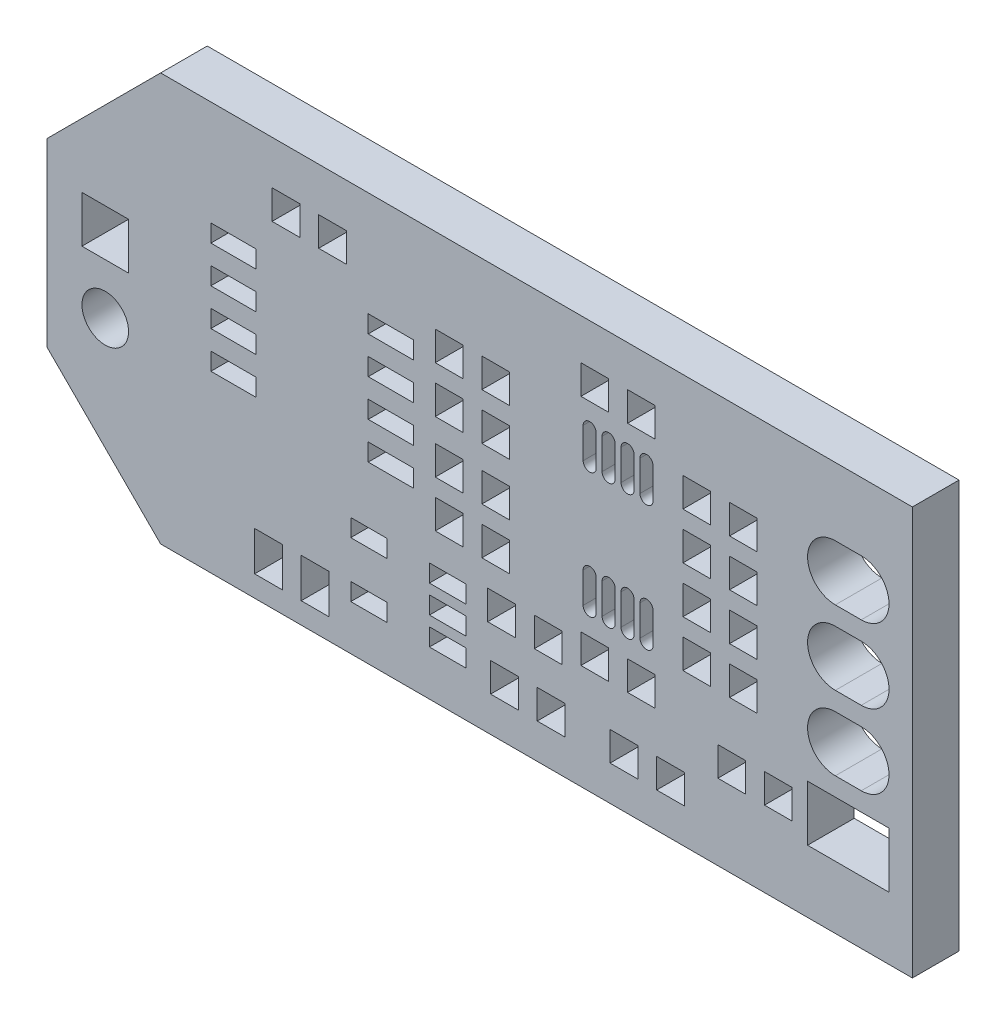
SolidWorks part; units mm, degrees
ref_plane "Front Plane" through (0, 0, 0) normal (0, 0, 1) x (1, 0, 0)
ref_plane "Top Plane" through (0, 0, 0) normal (0, 1, 0) x (1, 0, 0)
ref_plane "Right Plane" through (0, 0, 0) normal (1, 0, 0) x (0, 0, -1)
sketch "Model" plane through (0, 0, 0) normal (0, 0, 1) x (1, 0, 0)
  line L0 (-135.5251, 26.45) -> (-135.5251, 25.85)
  line L1 (-135.5251, 25.85) -> (-136.775, 25.85)
  line L2 (-136.775, 25.85) -> (-136.775, 26.45)
  line L3 (-136.775, 26.45) -> (-135.5251, 26.45)
  line L4 (-135.5251, 27.4) -> (-135.5251, 26.8)
  line L5 (-135.5251, 26.8) -> (-136.775, 26.8)
  line L6 (-136.775, 26.8) -> (-136.775, 27.4)
  line L7 (-136.775, 27.4) -> (-135.5251, 27.4)
  line L8 (-135.5251, 28.3499) -> (-135.5251, 27.7501)
  line L9 (-135.5251, 27.7501) -> (-136.775, 27.7501)
  line L10 (-136.775, 27.7501) -> (-136.775, 28.3499)
  line L11 (-136.775, 28.3499) -> (-135.5251, 28.3499)
  line L12 (-138.2251, 28.3499) -> (-138.2251, 27.7501)
  line L13 (-138.2251, 27.7501) -> (-139.475, 27.7501)
  line L14 (-139.475, 27.7501) -> (-139.475, 28.3499)
  line L15 (-139.475, 28.3499) -> (-138.2251, 28.3499)
  line L16 (-138.2251, 26.45) -> (-138.2251, 25.85)
  line L17 (-138.2251, 25.85) -> (-139.475, 25.85)
  line L18 (-139.475, 25.85) -> (-139.475, 26.45)
  line L19 (-139.475, 26.45) -> (-138.2251, 26.45)
  line L22 (-135.25, 28.9) -> (-135.25, 25.3)
  line L23 (-135.25, 25.3) -> (-139.75, 25.3)
  line L24 (-139.75, 25.3) -> (-139.75, 28.9)
  line L25 (-139.75, 28.9) -> (-135.25, 28.9)
  line L26 (-121.003, 26.4475) -> (-123.797, 26.4475)
  line L27 (-123.797, 26.4475) -> (-123.797, 28.3525)
  line L28 (-123.797, 28.3525) -> (-121.003, 28.3525)
  line L29 (-121.003, 28.3525) -> (-121.003, 26.4475)
  line L30 (-122.8445, 30.8925) -> (-121.9555, 30.8925)
  line L31 (-121.9555, 28.9875) -> (-122.8445, 28.9875)
  line L32 (-122.8445, 33.4325) -> (-121.9555, 33.4325)
  line L33 (-121.9555, 31.5275) -> (-122.8445, 31.5275)
  line L34 (-122.8445, 35.9725) -> (-121.9555, 35.9725)
  line L35 (-121.9555, 34.0675) -> (-122.8445, 34.0675)
  line L38 (-148.7, 33.4) -> (-147.1, 33.4)
  line L39 (-147.1, 33.4) -> (-147.1, 31.8)
  line L40 (-147.1, 31.8) -> (-148.7, 31.8)
  line L41 (-148.7, 31.8) -> (-148.7, 33.4)
  line L44 (-149.295, 33.995) -> (-146.505, 33.995)
  line L45 (-146.505, 33.995) -> (-146.505, 28.665)
  line L46 (-146.505, 28.665) -> (-149.295, 28.665)
  line L47 (-149.295, 28.665) -> (-149.295, 33.995)
  line L48 (-141.825, 25.025) -> (-142.775, 25.025)
  line L49 (-142.775, 25.025) -> (-142.775, 26.375)
  line L50 (-142.775, 26.375) -> (-141.825, 26.375)
  line L51 (-141.825, 26.375) -> (-141.825, 25.025)
  line L52 (-140.225, 25.025) -> (-141.175, 25.025)
  line L53 (-141.175, 25.025) -> (-141.175, 26.375)
  line L54 (-141.175, 26.375) -> (-140.225, 26.375)
  line L55 (-140.225, 26.375) -> (-140.225, 25.025)
  line L58 (-142.9, 24.85) -> (-142.9, 26.55)
  line L59 (-142.9, 26.55) -> (-140.1, 26.55)
  line L60 (-140.1, 26.55) -> (-140.1, 24.85)
  line L61 (-140.1, 24.85) -> (-142.9, 24.85)
  line L62 (-131.05, 30.775) -> (-131.05, 29.725)
  line L63 (-131.5, 29.725) -> (-131.5, 30.775)
  line L64 (-130.4, 30.775) -> (-130.4, 29.725)
  line L65 (-130.85, 29.725) -> (-130.85, 30.775)
  line L66 (-129.75, 30.775) -> (-129.75, 29.725)
  line L67 (-130.2, 29.725) -> (-130.2, 30.775)
  line L68 (-129.1, 30.775) -> (-129.1, 29.725)
  line L69 (-129.55, 29.725) -> (-129.55, 30.775)
  line L70 (-129.1, 35.075) -> (-129.1, 34.025)
  line L71 (-129.55, 34.025) -> (-129.55, 35.075)
  line L72 (-129.75, 35.075) -> (-129.75, 34.025)
  line L73 (-130.2, 34.025) -> (-130.2, 35.075)
  line L74 (-130.4, 35.075) -> (-130.4, 34.025)
  line L75 (-130.85, 34.025) -> (-130.85, 35.075)
  line L76 (-131.05, 35.075) -> (-131.05, 34.025)
  line L77 (-131.5, 34.025) -> (-131.5, 35.075)
  line L80 (-128.5, 29.25) -> (-132.1, 29.25)
  line L81 (-132.1, 29.25) -> (-132.1, 35.55)
  line L82 (-132.1, 35.55) -> (-128.5, 35.55)
  line L83 (-128.5, 35.55) -> (-128.5, 29.25)
  line L84 (-125.925, 26.9) -> (-126.875, 26.9)
  line L85 (-126.875, 26.9) -> (-126.875, 27.9)
  line L86 (-126.875, 27.9) -> (-125.925, 27.9)
  line L87 (-125.925, 27.9) -> (-125.925, 26.9)
  line L88 (-124.325, 26.9) -> (-125.275, 26.9)
  line L89 (-125.275, 26.9) -> (-125.275, 27.9)
  line L90 (-125.275, 27.9) -> (-124.325, 27.9)
  line L91 (-124.325, 27.9) -> (-124.325, 26.9)
  line L94 (-127.15, 26.65) -> (-127.15, 28.15)
  line L95 (-127.15, 28.15) -> (-124.05, 28.15)
  line L96 (-124.05, 28.15) -> (-124.05, 26.65)
  line L97 (-124.05, 26.65) -> (-127.15, 26.65)
  line L98 (-133.725, 25.5) -> (-134.675, 25.5)
  line L99 (-134.675, 25.5) -> (-134.675, 26.5)
  line L100 (-134.675, 26.5) -> (-133.725, 26.5)
  line L101 (-133.725, 26.5) -> (-133.725, 25.5)
  line L102 (-132.125, 25.5) -> (-133.075, 25.5)
  line L103 (-133.075, 25.5) -> (-133.075, 26.5)
  line L104 (-133.075, 26.5) -> (-132.125, 26.5)
  line L105 (-132.125, 26.5) -> (-132.125, 25.5)
  line L108 (-134.95, 25.25) -> (-134.95, 26.75)
  line L109 (-134.95, 26.75) -> (-131.85, 26.75)
  line L110 (-131.85, 26.75) -> (-131.85, 25.25)
  line L111 (-131.85, 25.25) -> (-134.95, 25.25)
  line L112 (-133.825, 27.6) -> (-134.775, 27.6)
  line L113 (-134.775, 27.6) -> (-134.775, 28.6)
  line L114 (-134.775, 28.6) -> (-133.825, 28.6)
  line L115 (-133.825, 28.6) -> (-133.825, 27.6)
  line L116 (-132.225, 27.6) -> (-133.175, 27.6)
  line L117 (-133.175, 27.6) -> (-133.175, 28.6)
  line L118 (-133.175, 28.6) -> (-132.225, 28.6)
  line L119 (-132.225, 28.6) -> (-132.225, 27.6)
  line L122 (-135.05, 27.35) -> (-135.05, 28.85)
  line L123 (-135.05, 28.85) -> (-131.95, 28.85)
  line L124 (-131.95, 28.85) -> (-131.95, 27.35)
  line L125 (-131.95, 27.35) -> (-135.05, 27.35)
  line L126 (-128.975, 26.5) -> (-128.025, 26.5)
  line L127 (-128.025, 26.5) -> (-128.025, 25.5)
  line L128 (-128.025, 25.5) -> (-128.975, 25.5)
  line L129 (-128.975, 25.5) -> (-128.975, 26.5)
  line L130 (-130.575, 26.5) -> (-129.625, 26.5)
  line L131 (-129.625, 26.5) -> (-129.625, 25.5)
  line L132 (-129.625, 25.5) -> (-130.575, 25.5)
  line L133 (-130.575, 25.5) -> (-130.575, 26.5)
  line L136 (-127.75, 26.75) -> (-127.75, 25.25)
  line L137 (-127.75, 25.25) -> (-130.85, 25.25)
  line L138 (-130.85, 25.25) -> (-130.85, 26.75)
  line L139 (-130.85, 26.75) -> (-127.75, 26.75)
  line L140 (-127.125, 29.5) -> (-128.075, 29.5)
  line L141 (-128.075, 29.5) -> (-128.075, 30.5)
  line L142 (-128.075, 30.5) -> (-127.125, 30.5)
  line L143 (-127.125, 30.5) -> (-127.125, 29.5)
  line L144 (-125.525, 29.5) -> (-126.475, 29.5)
  line L145 (-126.475, 29.5) -> (-126.475, 30.5)
  line L146 (-126.475, 30.5) -> (-125.525, 30.5)
  line L147 (-125.525, 30.5) -> (-125.525, 29.5)
  line L150 (-128.35, 29.25) -> (-128.35, 30.75)
  line L151 (-128.35, 30.75) -> (-125.25, 30.75)
  line L152 (-125.25, 30.75) -> (-125.25, 29.25)
  line L153 (-125.25, 29.25) -> (-128.35, 29.25)
  line L154 (-127.125, 34.3) -> (-128.075, 34.3)
  line L155 (-128.075, 34.3) -> (-128.075, 35.3)
  line L156 (-128.075, 35.3) -> (-127.125, 35.3)
  line L157 (-127.125, 35.3) -> (-127.125, 34.3)
  line L158 (-125.525, 34.3) -> (-126.475, 34.3)
  line L159 (-126.475, 34.3) -> (-126.475, 35.3)
  line L160 (-126.475, 35.3) -> (-125.525, 35.3)
  line L161 (-125.525, 35.3) -> (-125.525, 34.3)
  line L164 (-128.35, 34.05) -> (-128.35, 35.55)
  line L165 (-128.35, 35.55) -> (-125.25, 35.55)
  line L166 (-125.25, 35.55) -> (-125.25, 34.05)
  line L167 (-125.25, 34.05) -> (-128.35, 34.05)
  line L168 (-127.125, 31.1) -> (-128.075, 31.1)
  line L169 (-128.075, 31.1) -> (-128.075, 32.1)
  line L170 (-128.075, 32.1) -> (-127.125, 32.1)
  line L171 (-127.125, 32.1) -> (-127.125, 31.1)
  line L172 (-125.525, 31.1) -> (-126.475, 31.1)
  line L173 (-126.475, 31.1) -> (-126.475, 32.1)
  line L174 (-126.475, 32.1) -> (-125.525, 32.1)
  line L175 (-125.525, 32.1) -> (-125.525, 31.1)
  line L178 (-128.35, 30.85) -> (-128.35, 32.35)
  line L179 (-128.35, 32.35) -> (-125.25, 32.35)
  line L180 (-125.25, 32.35) -> (-125.25, 30.85)
  line L181 (-125.25, 30.85) -> (-128.35, 30.85)
  line L182 (-127.125, 32.7) -> (-128.075, 32.7)
  line L183 (-128.075, 32.7) -> (-128.075, 33.7)
  line L184 (-128.075, 33.7) -> (-127.125, 33.7)
  line L185 (-127.125, 33.7) -> (-127.125, 32.7)
  line L186 (-125.525, 32.7) -> (-126.475, 32.7)
  line L187 (-126.475, 32.7) -> (-126.475, 33.7)
  line L188 (-126.475, 33.7) -> (-125.525, 33.7)
  line L189 (-125.525, 33.7) -> (-125.525, 32.7)
  line L192 (-128.35, 32.45) -> (-128.35, 33.95)
  line L193 (-128.35, 33.95) -> (-125.25, 33.95)
  line L194 (-125.25, 33.95) -> (-125.25, 32.45)
  line L195 (-125.25, 32.45) -> (-128.35, 32.45)
  line L196 (-135.625, 34.4) -> (-136.575, 34.4)
  line L197 (-136.575, 34.4) -> (-136.575, 35.4)
  line L198 (-136.575, 35.4) -> (-135.625, 35.4)
  line L199 (-135.625, 35.4) -> (-135.625, 34.4)
  line L200 (-134.025, 34.4) -> (-134.975, 34.4)
  line L201 (-134.975, 34.4) -> (-134.975, 35.4)
  line L202 (-134.975, 35.4) -> (-134.025, 35.4)
  line L203 (-134.025, 35.4) -> (-134.025, 34.4)
  line L206 (-136.85, 34.15) -> (-136.85, 35.65)
  line L207 (-136.85, 35.65) -> (-133.75, 35.65)
  line L208 (-133.75, 35.65) -> (-133.75, 34.15)
  line L209 (-133.75, 34.15) -> (-136.85, 34.15)
  line L210 (-135.625, 29.4) -> (-136.575, 29.4)
  line L211 (-136.575, 29.4) -> (-136.575, 30.4)
  line L212 (-136.575, 30.4) -> (-135.625, 30.4)
  line L213 (-135.625, 30.4) -> (-135.625, 29.4)
  line L214 (-134.025, 29.4) -> (-134.975, 29.4)
  line L215 (-134.975, 29.4) -> (-134.975, 30.4)
  line L216 (-134.975, 30.4) -> (-134.025, 30.4)
  line L217 (-134.025, 30.4) -> (-134.025, 29.4)
  line L220 (-136.85, 29.15) -> (-136.85, 30.65)
  line L221 (-136.85, 30.65) -> (-133.75, 30.65)
  line L222 (-133.75, 30.65) -> (-133.75, 29.15)
  line L223 (-133.75, 29.15) -> (-136.85, 29.15)
  line L224 (-130.625, 35.9) -> (-131.575, 35.9)
  line L225 (-131.575, 35.9) -> (-131.575, 36.9)
  line L226 (-131.575, 36.9) -> (-130.625, 36.9)
  line L227 (-130.625, 36.9) -> (-130.625, 35.9)
  line L228 (-129.025, 35.9) -> (-129.975, 35.9)
  line L229 (-129.975, 35.9) -> (-129.975, 36.9)
  line L230 (-129.975, 36.9) -> (-129.025, 36.9)
  line L231 (-129.025, 36.9) -> (-129.025, 35.9)
  line L234 (-131.85, 35.65) -> (-131.85, 37.15)
  line L235 (-131.85, 37.15) -> (-128.75, 37.15)
  line L236 (-128.75, 37.15) -> (-128.75, 35.65)
  line L237 (-128.75, 35.65) -> (-131.85, 35.65)
  line L238 (-130.625, 27.9) -> (-131.575, 27.9)
  line L239 (-131.575, 27.9) -> (-131.575, 28.9)
  line L240 (-131.575, 28.9) -> (-130.625, 28.9)
  line L241 (-130.625, 28.9) -> (-130.625, 27.9)
  line L242 (-129.025, 27.9) -> (-129.975, 27.9)
  line L243 (-129.975, 27.9) -> (-129.975, 28.9)
  line L244 (-129.975, 28.9) -> (-129.025, 28.9)
  line L245 (-129.025, 28.9) -> (-129.025, 27.9)
  line L248 (-131.85, 27.65) -> (-131.85, 29.15)
  line L249 (-131.85, 29.15) -> (-128.75, 29.15)
  line L250 (-128.75, 29.15) -> (-128.75, 27.65)
  line L251 (-128.75, 27.65) -> (-131.85, 27.65)
  line L252 (-134.975, 32) -> (-134.025, 32)
  line L253 (-134.025, 32) -> (-134.025, 31)
  line L254 (-134.025, 31) -> (-134.975, 31)
  line L255 (-134.975, 31) -> (-134.975, 32)
  line L256 (-136.575, 32) -> (-135.625, 32)
  line L257 (-135.625, 32) -> (-135.625, 31)
  line L258 (-135.625, 31) -> (-136.575, 31)
  line L259 (-136.575, 31) -> (-136.575, 32)
  line L262 (-133.75, 32.25) -> (-133.75, 30.75)
  line L263 (-133.75, 30.75) -> (-136.85, 30.75)
  line L264 (-136.85, 30.75) -> (-136.85, 32.25)
  line L265 (-136.85, 32.25) -> (-133.75, 32.25)
  line L266 (-134.975, 33.8) -> (-134.025, 33.8)
  line L267 (-134.025, 33.8) -> (-134.025, 32.8)
  line L268 (-134.025, 32.8) -> (-134.975, 32.8)
  line L269 (-134.975, 32.8) -> (-134.975, 33.8)
  line L270 (-136.575, 33.8) -> (-135.625, 33.8)
  line L271 (-135.625, 33.8) -> (-135.625, 32.8)
  line L272 (-135.625, 32.8) -> (-136.575, 32.8)
  line L273 (-136.575, 32.8) -> (-136.575, 33.8)
  line L276 (-133.75, 34.05) -> (-133.75, 32.55)
  line L277 (-133.75, 32.55) -> (-136.85, 32.55)
  line L278 (-136.85, 32.55) -> (-136.85, 34.05)
  line L279 (-136.85, 34.05) -> (-133.75, 34.05)
  line L280 (-141.225, 35.8) -> (-142.175, 35.8)
  line L281 (-142.175, 35.8) -> (-142.175, 36.8)
  line L282 (-142.175, 36.8) -> (-141.225, 36.8)
  line L283 (-141.225, 36.8) -> (-141.225, 35.8)
  line L284 (-139.625, 35.8) -> (-140.575, 35.8)
  line L285 (-140.575, 35.8) -> (-140.575, 36.8)
  line L286 (-140.575, 36.8) -> (-139.625, 36.8)
  line L287 (-139.625, 36.8) -> (-139.625, 35.8)
  line L290 (-142.45, 35.55) -> (-142.45, 37.05)
  line L291 (-142.45, 37.05) -> (-139.35, 37.05)
  line L292 (-139.35, 37.05) -> (-139.35, 35.55)
  line L293 (-139.35, 35.55) -> (-142.45, 35.55)
  line L294 (-144.275, 34.105) -> (-144.275, 34.705)
  line L295 (-144.275, 34.705) -> (-142.725, 34.705)
  line L296 (-142.725, 34.705) -> (-142.725, 34.105)
  line L297 (-142.725, 34.105) -> (-144.275, 34.105)
  line L298 (-144.275, 32.835) -> (-144.275, 33.435)
  line L299 (-144.275, 33.435) -> (-142.725, 33.435)
  line L300 (-142.725, 33.435) -> (-142.725, 32.835)
  line L301 (-142.725, 32.835) -> (-144.275, 32.835)
  line L302 (-144.275, 31.565) -> (-144.275, 32.165)
  line L303 (-144.275, 32.165) -> (-142.725, 32.165)
  line L304 (-142.725, 32.165) -> (-142.725, 31.565)
  line L305 (-142.725, 31.565) -> (-144.275, 31.565)
  line L306 (-144.275, 30.295) -> (-144.275, 30.895)
  line L307 (-144.275, 30.895) -> (-142.725, 30.895)
  line L308 (-142.725, 30.895) -> (-142.725, 30.295)
  line L309 (-142.725, 30.295) -> (-144.275, 30.295)
  line L310 (-138.875, 30.295) -> (-138.875, 30.895)
  line L311 (-138.875, 30.895) -> (-137.325, 30.895)
  line L312 (-137.325, 30.895) -> (-137.325, 30.295)
  line L313 (-137.325, 30.295) -> (-138.875, 30.295)
  line L314 (-138.875, 31.565) -> (-138.875, 32.165)
  line L315 (-138.875, 32.165) -> (-137.325, 32.165)
  line L316 (-137.325, 32.165) -> (-137.325, 31.565)
  line L317 (-137.325, 31.565) -> (-138.875, 31.565)
  line L318 (-138.875, 32.835) -> (-138.875, 33.435)
  line L319 (-138.875, 33.435) -> (-137.325, 33.435)
  line L320 (-137.325, 33.435) -> (-137.325, 32.835)
  line L321 (-137.325, 32.835) -> (-138.875, 32.835)
  line L322 (-138.875, 34.105) -> (-138.875, 34.705)
  line L323 (-138.875, 34.705) -> (-137.325, 34.705)
  line L324 (-137.325, 34.705) -> (-137.325, 34.105)
  line L325 (-137.325, 34.105) -> (-138.875, 34.105)
  line L328 (-144.55, 29.75) -> (-144.55, 35.25)
  line L329 (-144.55, 35.25) -> (-137.05, 35.25)
  line L330 (-137.05, 35.25) -> (-137.05, 29.75)
  line L331 (-137.05, 29.75) -> (-144.55, 29.75)
  line L332 (-146, 24.3) -> (-120.2, 24.3)
  line L333 (-120.2, 24.3) -> (-120.2, 38.3)
  line L334 (-120.2, 38.3) -> (-146, 38.3)
  line L335 (-146, 38.3) -> (-149.9, 34.4)
  line L336 (-149.9, 34.4) -> (-149.9, 28.2)
  line L337 (-149.9, 28.2) -> (-146, 24.3)
  circle A0 centre (-147.9, 30.06) radius 0.8
  arc A2 (-121.9555, 28.9875) -> (-121.9555, 30.8925) centre (-121.9555, 29.94) ccw
  arc A3 (-122.8445, 30.8925) -> (-122.8445, 28.9875) centre (-122.8445, 29.94) ccw
  arc A4 (-121.9555, 31.5275) -> (-121.9555, 33.4325) centre (-121.9555, 32.48) ccw
  arc A5 (-122.8445, 33.4325) -> (-122.8445, 31.5275) centre (-122.8445, 32.48) ccw
  arc A6 (-121.9555, 34.0675) -> (-121.9555, 35.9725) centre (-121.9555, 35.02) ccw
  arc A7 (-122.8445, 35.9725) -> (-122.8445, 34.0675) centre (-122.8445, 35.02) ccw
  arc A11 (-131.5, 29.725) -> (-131.05, 29.725) centre (-131.275, 29.725) ccw
  arc A12 (-131.05, 30.775) -> (-131.5, 30.775) centre (-131.275, 30.775) ccw
  arc A13 (-130.85, 29.725) -> (-130.4, 29.725) centre (-130.625, 29.725) ccw
  arc A14 (-130.4, 30.775) -> (-130.85, 30.775) centre (-130.625, 30.775) ccw
  arc A15 (-130.2, 29.725) -> (-129.75, 29.725) centre (-129.975, 29.725) ccw
  arc A16 (-129.75, 30.775) -> (-130.2, 30.775) centre (-129.975, 30.775) ccw
  arc A17 (-129.55, 29.725) -> (-129.1, 29.725) centre (-129.325, 29.725) ccw
  arc A18 (-129.1, 30.775) -> (-129.55, 30.775) centre (-129.325, 30.775) ccw
  arc A19 (-129.55, 34.025) -> (-129.1, 34.025) centre (-129.325, 34.025) ccw
  arc A20 (-129.1, 35.075) -> (-129.55, 35.075) centre (-129.325, 35.075) ccw
  arc A21 (-130.2, 34.025) -> (-129.75, 34.025) centre (-129.975, 34.025) ccw
  arc A22 (-129.75, 35.075) -> (-130.2, 35.075) centre (-129.975, 35.075) ccw
  arc A23 (-130.85, 34.025) -> (-130.4, 34.025) centre (-130.625, 34.025) ccw
  arc A24 (-130.4, 35.075) -> (-130.85, 35.075) centre (-130.625, 35.075) ccw
  arc A25 (-131.5, 34.025) -> (-131.05, 34.025) centre (-131.275, 34.025) ccw
  arc A26 (-131.05, 35.075) -> (-131.5, 35.075) centre (-131.275, 35.075) ccw
extrude "Boss-Extrude1" add sketch "Model" along normal blind 1.6 contours L336 L337 L332 L333 L334 L335 A7 L34 A6 L35 A5 L32 A4 L33 A3 L30 A2 L31 L330 L331 L328 L329 L278 L279 L276 L277 L250 L251 L248 L249 L222 L223 L220 L221 L194 L195 L192 L193 L166 L167 L164 L165 | L83 L82 L81 L80 A26 L76 A25 L77 A24 L74 A23 L75 A22 L72 A21 L73 A20 L70 A19 L71 A18 L68 A17 L69 A16 L66 A15 L67 A14 L64 A13 L65 A12 L62 A11 L63 | L97 L96 L95 L94 L86 L87 L84 L85 L90 L91 L88 L89 | L251 L250 L249 L248 L240 L241 L238 L239 L244 L245 L242 L243 | L139 L138 L137 L136 L128 L129 L126 L127 L132 L133 L130 L131 | L125 L124 L123 L122 L114 L115 L112 L113 L118 L119 L116 L117 | L111 L110 L109 L108 L100 L101 L98 L99 L104 L105 L102 L103 | L25 L24 L23 L22 L2 L3 L0 L1 L6 L7 L4 L5 L10 L11 L8 L9 L14 L15 L12 L13 L18 L19 L16 L17 | L331 L330 L329 L328 L296 L297 L294 L295 L300 L301 L298 L299 L304 L305 L302 L303 L308 L309 L306 L307 L312 L313 L310 L311 L316 L317 L314 L315 L320 L321 L318 L319 L324 L325 L322 L323 | L47 L46 L45 L44 A0 L40 L41 L38 L39 | L61 L60 L59 L58 L50 L51 L48 L49 L54 L55 L52 L53 | L293 L292 L291 L290 L282 L283 L280 L281 L286 L287 L284 L285 | L237 L236 L235 L234 L226 L227 L224 L225 L230 L231 L228 L229 | L209 L208 L207 L206 L198 L199 L196 L197 L202 L203 L200 L201 | L279 L278 L277 L276 L268 L269 L266 L267 L272 L273 L270 L271 | L265 L264 L263 L262 L254 L255 L252 L253 L258 L259 L256 L257 | L223 L222 L221 L220 L212 L213 L210 L211 L216 L217 L214 L215 | L153 L152 L151 L150 L142 L143 L140 L141 L146 L147 L144 L145 | L181 L180 L179 L178 L170 L171 L168 L169 L174 L175 L172 L173 | L195 L194 L193 L192 L184 L185 L182 L183 L188 L189 L186 L187 | L167 L166 L165 L164 L156 L157 L154 L155 L160 L161 L158 L159
